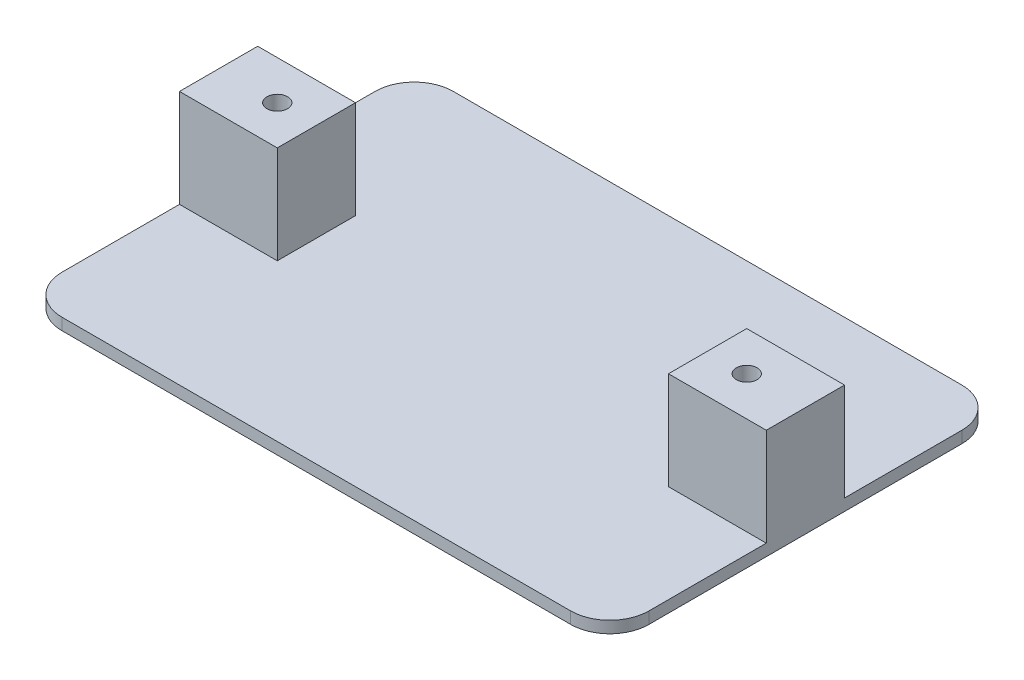
SolidWorks part; units mm, degrees
ref_plane "Front Plane" through (0, 0, 0) normal (0, 0, 1) x (1, 0, 0)
ref_plane "Top Plane" through (0, 0, 0) normal (0, 1, 0) x (1, 0, 0)
ref_plane "Right Plane" through (0, 0, 0) normal (1, 0, 0) x (0, 0, -1)
sketch "Sketch1" plane through (0, 0, 0) normal (0, 1, 0) x (1, 0, 0)
  line L0 (-75, 0) -> (-60, 0) construction
  line L1 (-75, -50) -> (75, -50)
  line L2 (-75, -50) -> (-75, 50)
  line L3 (-75, 50) -> (75, 50)
  line L4 (75, -50) -> (75, 50)
  line L5 (-75, -50) -> (75, 50) construction
  line L6 (-75, 50) -> (75, -50) construction
  line L7 (75, 0) -> (60, 0) construction
  circle A0 centre (-60, 0) radius 2.6
  circle A1 centre (60, 0) radius 2.6
  point P0 (0, 0)
  dimension "D1" = 150
  dimension "D2" = 100
  dimension "D3" = 15
  dimension "D4" = 15
extrude "Boss-Extrude1" add sketch "Sketch1" along normal blind 3
sketch "Sketch2" plane through (0, 3, 0) normal (0, 1, 0) x (1, 0, 0)
  line L0 (-75, 50) -> (-75, -50) construction
  line L1 (-70, -10) -> (-50, -10)
  line L3 (-70, 10) -> (-50, 10)
  line L4 (-50, -10) -> (-50, 10)
  line L5 (-70, -10) -> (-50, 10) construction
  line L6 (-70, 10) -> (-50, -10) construction
  line L7 (49.9976, -10.0024) -> (70.0024, -10.0024)
  line L8 (49.9976, -10.0024) -> (49.9976, 10.0024)
  line L9 (49.9976, 10.0024) -> (70.0024, 10.0024)
  line L11 (49.9976, -10.0024) -> (70.0024, 10.0024) construction
  line L12 (49.9976, 10.0024) -> (70.0024, -10.0024) construction
  line L13 (-70, 10) -> (-75, 10)
  line L15 (-70, -10) -> (-75, -10)
  line L16 (-75, 10) -> (-75, -10)
  line L17 (75, -50) -> (75, 50) construction
  line L18 (70.0024, 10.0024) -> (75, 10.0024)
  line L20 (70.0024, -10.0024) -> (75, -10.0024)
  line L21 (75, 10.0024) -> (75, -10.0024)
  circle A0 centre (-60, 0) radius 2.65
  circle A1 centre (60, 0) radius 2.65
  point P0 (-60, 0)
  point P5 (60, 0)
extrude "Boss-Extrude2" add sketch "Sketch2" along normal blind 25
fillet "Fillet1" radius 10 4 edges at (-75, 1.5, -50) (75, 1.5, -50) (75, 1.5, 50) (-75, 1.5, 50)
